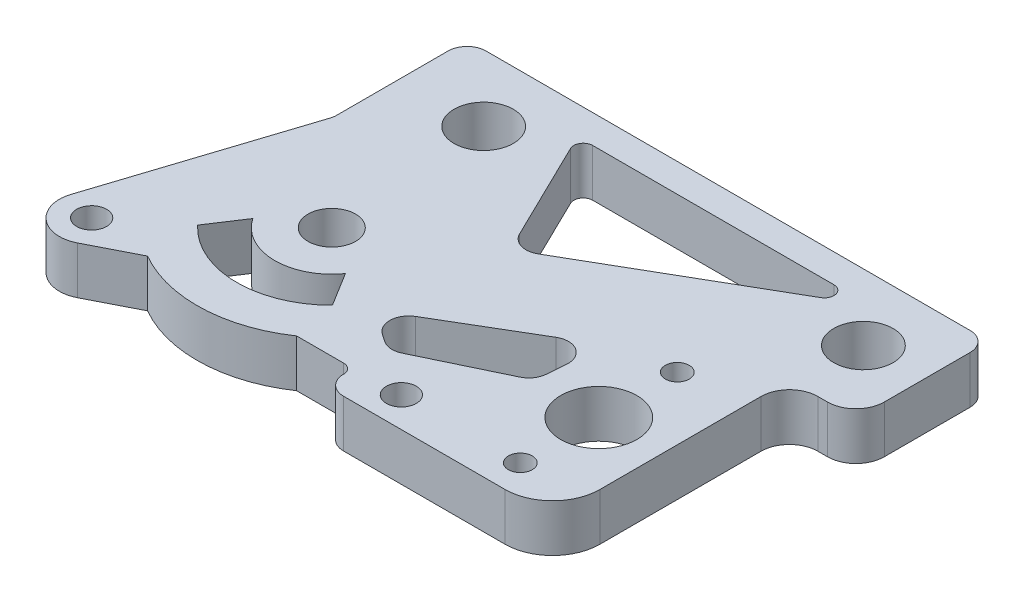
SolidWorks part; units mm, degrees
material "7075-T6 (SN)"
ref_plane "X-Y Datum" through (0, 0, 0) normal (0, 0, 1) x (1, 0, 0)
ref_plane "X-Z Datum" through (0, 0, 0) normal (0, 1, 0) x (1, 0, 0)
ref_plane "Y-Z Datum" through (0, 0, 0) normal (1, 0, 0) x (0, 0, -1)
other "Graphic1"
other "Graphic (Closed) -1"
other "Graphic (Closed) -2"
sketch "Sketch2" plane through (0, 0, 0) normal (0, 1, 0) x (1, 0, 0)
  line L0 (48.6426, -18.7325) -> (-23.0162, -18.7325)
  line L1 (24.0125, -14.7036) -> (25.7865, -13.7801) construction
  line L2 (0, 0) -> (105.5557, -202.7707) construction
  line L3 (11.142, -21.4036) -> (-3.5026, -29.027) construction
  line L4 (0, 0) -> (0, -121.3797) construction
  line L5 (-3.5026, -29.027) -> (90.9112, -210.3941) construction
  line L6 (90.9112, -210.3941) -> (105.5557, -202.7707) construction
  line L7 (11.142, -21.4036) -> (24.0125, -14.7036) construction
  line L11 (-12.7, 30.7975) -> (57.15, 30.7975)
  line L12 (57.15, 13.0175) -> (57.15, 30.7975)
  line L13 (57.15, 13.0175) -> (-12.7, 13.0175) construction
  line L15 (44.7685, -18.0975) -> (44.7685, -11.3157) construction
  line L16 (44.7685, -18.0975) -> (34.8625, -18.0975) construction
  line L18 (44.7685, 9.8425) -> (34.8625, 9.8425) construction
  line L20 (44.7685, -11.3157) -> (49.8485, -11.3157) construction
  line L21 (49.8485, -11.3157) -> (49.8485, 3.0607) construction
  line L22 (49.8485, 3.0607) -> (44.7685, 3.0607) construction
  line L23 (44.7685, 3.0607) -> (44.7685, 9.8425) construction
  line L24 (34.8625, -18.0975) -> (34.8625, 9.8425) construction
  line L25 (48.6426, -18.7325) -> (57.15, 13.0175)
  line L26 (-12.7, 30.7975) -> (-12.7, 13.0175)
  line L28 (-12.5603, 0) -> (-16.51, -40.5272) construction
  line L30 (-23.0162, -18.7325) -> (-12.7, 13.0175)
  circle A0 centre (0, 0) radius 3.175
  circle A1 centre (24.0125, -14.7036) radius 2
  circle A2 centre (-1.5875, 21.9075) radius 3.9688
  circle A3 centre (49.2125, 21.9075) radius 3.9687
  circle A4 centre (39.8485, -4.1275) radius 5.1
  circle A5 centre (24.0125, -14.7036) radius 3.175 construction
  circle A6 centre (39.8485, -14.6275) radius 1.6
  circle A7 centre (39.8485, 6.3725) radius 1.6
  circle A8 centre (-17.2047, -14.9225) radius 3.175 construction
  circle A9 centre (-17.2047, -14.9225) radius 2
  point P9 (11.142, -21.4036)
  point P30 (49.8485, -4.1275)
  point P31 (34.8625, -4.1275)
  dimension "D1" = 6.35
  dimension "D8" = 4
  dimension "D10" = 7.9375
  dimension "D11" = 7.9375
  dimension "D16" = 27.94
  dimension "D23" = 10.2
  dimension "D20" = 6.35
  dimension "D30" = 3.2
  dimension "D32" = 3.2
  dimension "D34" = 6.35
  dimension "D35" = 4
  dimension "D3" = 13.0175
  dimension "D4" = 16.51
  dimension "D5" = 228.6
  dimension "D6" = 24.13
  dimension "D7" = 27.5
  dimension "D9" = 16.51
  dimension "D12" = 8.89
  dimension "D13" = 69.85
  dimension "D14" = 7.9375
  dimension "D15" = 31.75
  dimension "D17" = 17.78
  dimension "D18" = 3.175
  dimension "D19" = 14.986
  dimension "D21" = 5.08
  dimension "D22" = 14.3764
  dimension "D24" = 10
  dimension "D25" = 36.83
  dimension "D26" = 50.8
  dimension "D27" = 165
  dimension "D28" = 12.7
  dimension "D29" = 17.3015
  dimension "D31" = 10.5
  dimension "D33" = 10.5
  dimension "D36" = 162
extrude "Boss-Extrude1" [suppressed] add sketch "Sketch2" against normal blind 6.35
ref_point "Point1" [suppressed]
sketch "Sketch3" [suppressed] plane through (0, 0, 0) normal (0, 1, 0) x (1, 0, 0)
  line L0 (39.9681, 6.3725) -> (39.9681, -4.1275) construction
  line L1 (57.2697, 12.9663) -> (-12.5803, 12.9663) construction
  line L5 (39.9681, -4.1275) -> (39.9681, -14.6275) construction
  line L6 (42.0297, -18.7325) -> (20.4164, -18.7325)
  line L7 (57.2697, 12.9663) -> (57.2697, 30.7975)
  line L8 (57.2697, 30.7975) -> (-12.5803, 30.7975)
  line L9 (-12.5803, 30.7975) -> (-12.5803, 12.9663)
  line L10 (40.938, 24.6176) -> (16.9472, 10.7666)
  line L11 (13.3942, 11.8528) -> (6.9035, 25.1608)
  line L12 (8.045, 26.9875) -> (40.303, 26.9875)
  line L13 (57.2697, 12.9663) -> (48.3797, 12.9663)
  line L14 (48.3797, 12.9663) -> (48.3797, -12.3825)
  line L16 (-23.0162, -18.7325) -> (48.6426, -18.7325) construction
  line L18 (16.6064, -14.8627) -> (10.2787, -14.8627)
  line L21 (-8.965, -15.5427) -> (-15.106, -18.7325)
  line L24 (-21.1701, -13.6017) -> (-12.5803, 12.9663)
  line L29 (17.8764, -16.1925) -> (17.8764, -16.1327)
  circle A0 centre (0.1197, 0) radius 3.175
  circle A1 centre (-1.4678, 21.9075) radius 3.9688
  circle A2 centre (49.3322, 21.9075) radius 3.9687
  circle A3 centre (39.9681, -4.1275) radius 5.1
  circle A4 centre (39.9681, -14.6275) radius 1.6
  circle A5 centre (39.9681, 6.3725) radius 1.6
  circle A6 centre (24.1322, -14.7036) radius 2
  circle A7 centre (-17.085, -14.9225) radius 2
  arc A8 (13.3942, 11.8528) -> (16.9472, 10.7666) centre (15.6772, 12.9663) ccw
  arc A9 (8.045, 26.9875) -> (6.9035, 25.1608) centre (8.045, 25.7175) ccw
  arc A10 (40.938, 24.6176) -> (40.303, 26.9875) centre (40.303, 25.7175) ccw
  arc A11 (10.2787, -14.8627) -> (-8.965, -15.5427) centre (0.1197, 0) cw
  arc A12 (-15.106, -18.7325) -> (-21.1701, -13.6017) centre (-17.085, -14.9225) cw
  arc A13 (42.0297, -18.7325) -> (48.3797, -12.3825) centre (42.0297, -12.3825) ccw
  arc A14 (20.4164, -18.7325) -> (17.8764, -16.1925) centre (20.4164, -16.1925) cw
  arc A15 (16.6064, -14.8627) -> (17.8764, -16.1327) centre (16.6064, -16.1327) cw
  dimension "D1" = 6.35
  dimension "D4" = 7.9375
  dimension "D9" = 10.2
  dimension "D10" = 3.2
  dimension "D11" = 4
  dimension "D21" = 2.54
  dimension "D22" = 1.27
  dimension "D3" = 6.35
  dimension "D28" = 2.54
  dimension "D29" = 1.27
  dimension "D2" = 7.9375
  dimension "D5" = 50.8
  dimension "D6" = 21.9075
  dimension "D7" = 1.5875
  dimension "D8" = 8.89
  dimension "D12" = 10.5
  dimension "D13" = 17.2047
  dimension "D14" = 24.0125
  dimension "D15" = 14.7036
  dimension "D16" = 39.8485
  dimension "D17" = 4.1275
  dimension "D18" = 14.9225
  dimension "D19" = 69.85
  dimension "D20" = 3.81
  dimension "D23" = 30
  dimension "D24" = 64
  dimension "D25" = 32.258
  dimension "D26" = 15.5575
  dimension "D27" = 25.3488
  dimension "D30" = 8.89
sketch "Sketch4" plane through (0, 0, 0) normal (0, 1, 0) x (1, 0, 0)
  line L0 (39.8485, 6.3725) -> (39.8485, -4.1275) construction
  line L1 (57.15, 12.9663) -> (-12.7, 12.9663) construction
  line L2 (39.8485, -4.1275) -> (39.8485, -14.6275) construction
  line L3 (41.8868, -18.7325) -> (20.2968, -18.7325)
  line L4 (57.15, 16.7763) -> (57.15, 28.2575)
  line L5 (54.61, 30.7975) -> (-10.16, 30.7975)
  line L6 (-12.7, 28.2575) -> (-12.7, 13.3678)
  line L7 (40.8183, 24.6176) -> (16.8275, 10.7666)
  line L8 (13.2746, 11.8528) -> (6.7838, 25.1608)
  line L9 (7.9253, 26.9875) -> (40.1833, 26.9875)
  line L10 (53.34, 12.9663) -> (52.07, 12.9663)
  line L11 (48.26, 9.1563) -> (48.26, -12.3825)
  line L12 (16.4868, -14.8882) -> (10.1767, -14.8882)
  line L13 (-9.0404, -15.6044) -> (-15.2421, -18.7687)
  line L14 (-21.3121, -13.5905) -> (-12.8239, 12.5843)
  line L15 (17.7568, -16.1925) -> (17.7568, -16.1582)
  line L16 (31.3257, -2.6269) -> (31.5236, -0.0707)
  line L17 (27.6993, 2.3123) -> (15.8696, -4.676)
  line L18 (15.7254, -8.958) -> (16.6997, -9.6258)
  line L19 (19.2321, -9.8219) -> (29.8897, -4.722)
  line L20 (6.2229, -4.3977) -> (9.0222, -8.9381)
  line L21 (-6.35, -4.2121) -> (-9.282, -8.668)
  circle A0 centre (0, 0) radius 3.175
  circle A1 centre (-1.5875, 21.9075) radius 3.9688
  circle A2 centre (49.2125, 21.9075) radius 3.9687
  circle A3 centre (39.8485, -4.1275) radius 5.1
  circle A4 centre (39.8485, -14.6275) radius 1.6
  circle A5 centre (39.8485, 6.3725) radius 1.6
  circle A6 centre (24.0125, -14.7036) radius 2
  circle A7 centre (-17.2047, -14.9225) radius 2
  arc A8 (13.2746, 11.8528) -> (16.8275, 10.7666) centre (15.5575, 12.9663) ccw
  arc A9 (7.9253, 26.9875) -> (6.7838, 25.1608) centre (7.9253, 25.7175) ccw
  arc A10 (40.8183, 24.6176) -> (40.1833, 26.9875) centre (40.1833, 25.7175) ccw
  arc A11 (10.1767, -14.8882) -> (-9.0404, -15.6044) centre (0, 0) cw
  arc A12 (-15.2421, -18.7687) -> (-21.3121, -13.5905) centre (-17.2047, -14.9225) cw
  arc A13 (41.8868, -18.7325) -> (48.26, -12.3825) centre (41.91, -12.3825) ccw
  arc A14 (20.2968, -18.7325) -> (17.7568, -16.1925) centre (20.2968, -16.1925) cw
  arc A15 (16.4868, -14.8882) -> (17.7568, -16.1582) centre (16.4868, -16.1582) cw
  arc A16 (57.15, 16.7763) -> (53.34, 12.9663) centre (53.34, 16.7763) cw
  arc A17 (48.26, 9.1563) -> (52.07, 12.9663) centre (52.07, 9.1563) cw
  arc A18 (-12.7, 13.3678) -> (-12.8239, 12.5843) centre (-15.24, 13.3678) cw
  arc A19 (-12.7, 28.2575) -> (-10.16, 30.7975) centre (-10.16, 28.2575) cw
  arc A20 (54.61, 30.7975) -> (57.15, 28.2575) centre (54.61, 28.2575) cw
  arc A21 (16.6997, -9.6258) -> (19.2321, -9.8219) centre (18.1357, -7.5307) ccw
  arc A22 (29.8897, -4.722) -> (31.3257, -2.6269) centre (28.7933, -2.4308) ccw
  arc A23 (15.8696, -4.676) -> (15.7254, -8.958) centre (17.1615, -6.8629) ccw
  arc A24 (27.6993, 2.3123) -> (31.5236, -0.0707) centre (28.9912, 0.1254) cw
  arc A25 (6.2229, -4.3977) -> (-6.35, -4.2121) centre (0, 0) cw
  arc A26 (9.0222, -8.9381) -> (-9.282, -8.668) centre (0, 0) cw
  point P52 (48.26, 12.9663)
  point P58 (-12.7, 30.7975)
  point P61 (57.15, 30.7975)
  point P66 (17.9093, -10.4549)
  point P69 (31.2125, -4.089)
  point P72 (12.4368, -6.7039)
  point P75 (31.9003, 4.794)
  dimension "D1" = 6.35
  dimension "D2" = 7.9375
  dimension "D6" = 10.2
  dimension "D7" = 3.2
  dimension "D8" = 4
  dimension "D19" = 2.54
  dimension "D20" = 1.27
  dimension "D25" = 6.35
  dimension "D26" = 2.54
  dimension "D27" = 1.27
  dimension "D31" = 18.034
  dimension "D33" = 4.318
  dimension "D37" = 3.81
  dimension "D38" = 3.81
  dimension "D39" = 2.54
  dimension "D48" = 2.54
  dimension "D49" = 2.54
  dimension "D50" = 7.62
  dimension "D51" = 12.7
  dimension "D3" = 50.8
  dimension "D4" = 21.9075
  dimension "D5" = 1.5875
  dimension "D9" = 10.5
  dimension "D10" = 24.0125
  dimension "D11" = 14.7036
  dimension "D12" = 39.8485
  dimension "D13" = 4.1275
  dimension "D14" = 14.9225
  dimension "D15" = 17.2047
  dimension "D16" = 7.9375
  dimension "D17" = 8.89
  dimension "D18" = 3.81
  dimension "D21" = 30
  dimension "D22" = 64
  dimension "D23" = 32.258
  dimension "D24" = 15.5575
  dimension "D28" = 25.3488
  dimension "D29" = 8.89
  dimension "D30" = 21.59
  dimension "D32" = 45
  dimension "D34" = 69.85
  dimension "D35" = 23.0847
  dimension "D36" = 25.9645
  dimension "D40" = 55
  dimension "D41" = 65
  dimension "D42" = 120
  dimension "D43" = 8.636
  dimension "D44" = 22.606
  dimension "D45" = 4.2487
  dimension "D46" = 14.7479
  dimension "D47" = 31.9003
  dimension "D52" = 5.334
  dimension "D53" = 65
  dimension "D54" = 6.35
extrude "Boss-Extrude2" add sketch "Sketch4" against normal blind 6.35
ref_point "Point2"
ref_point "Point3"
